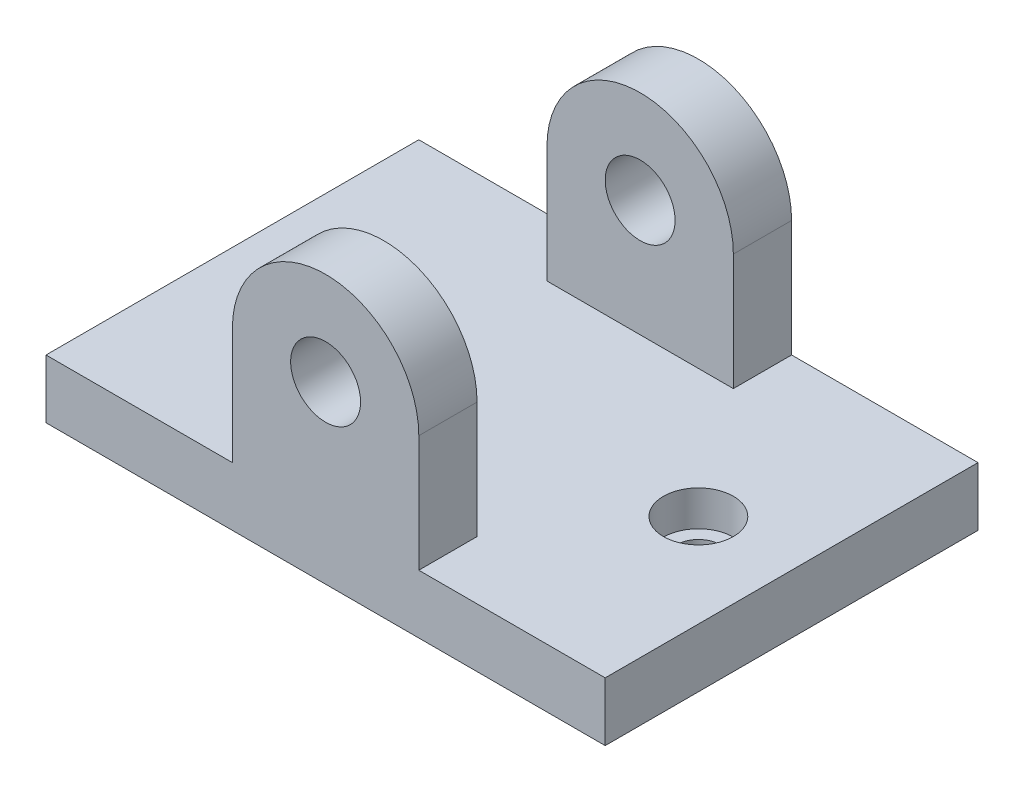
SolidWorks part; units mm, degrees
material "Plain Carbon Steel"
ref_plane "Front Plane" through (0, 0, 0) normal (0, 0, 1) x (1, 0, 0)
ref_plane "Top Plane" through (0, 0, 0) normal (0, 1, 0) x (1, 0, 0)
ref_plane "Right Plane" through (0, 0, 0) normal (1, 0, 0) x (0, 0, -1)
other "Configuration Table"
sketch "Sketch1" plane through (0, 0, 0) normal (0, 1, 0) x (1, 0, 0)
  line L1 (-76.2, 50.8) -> (76.2, 50.8)
  line L2 (-76.2, 50.8) -> (-76.2, -50.8)
  line L3 (-76.2, -50.8) -> (76.2, -50.8)
  line L4 (76.2, 50.8) -> (76.2, -50.8)
  line L5 (-76.2, 50.8) -> (76.2, -50.8) construction
  line L6 (-76.2, -50.8) -> (76.2, 50.8) construction
  point P0 (0, 0)
  dimension "D1" = 101.6
  dimension "D2" = 152.4
extrude "Boss-Extrude1" add sketch "Sketch1" along normal blind 16.002
sketch "Sketch2" plane through (0, 0, 0) normal (0, 1, 0) x (1, 0, 0)
  line L0 (-76.2, 0) -> (76.2, 0) construction
  line L1 (-76.2, 50.8) -> (-76.2, -50.8) construction
  line L2 (76.2, -50.8) -> (76.2, 50.8) construction
  line L3 (-50.8, 50.8) -> (-50.8, -50.8) construction
  line L4 (76.2, 50.8) -> (-76.2, 50.8) construction
  line L5 (-76.2, -50.8) -> (76.2, -50.8) construction
  line L6 (50.8, 50.8) -> (50.8, -50.8) construction
  dimension "D1" = 50.8
  dimension "D2" = 25.4
  dimension "D3" = 25.4
hole_wizard "CBORE for #0 Binding Head Machine Screw1" positions "Sketch3" profile "Sketch4" counterbore size "#0" standard "ANSI Inch" end condition through all
sketch "Sketch3" plane through (0, 16.002, 0) normal (0, 1, 0) x (1, 0, 0)
  line L0 (-76.2, 0) -> (76.2, 0) construction
  line L1 (-50.8, 50.8) -> (-50.8, -50.8) construction
  line L2 (50.8, 50.8) -> (50.8, -50.8) construction
  point P0 (-50.8, 0)
  point P6 (50.8, 0)
sketch "Sketch4" plane through (-50.8, 16.002, 0) normal (1, 0, 0) x (0, 0, 1)
  line L0 (0, 0) -> (0, 16.002)
  line L1 (0, 16.002) -> (5.9563, 16.002)
  line L3 (5.9563, 16.002) -> (5.9563, 9.652)
  line L4 (5.9563, 9.652) -> (9.525, 9.652)
  line L5 (9.525, 9.652) -> (9.525, 0)
  line L7 (9.525, 0) -> (0, 0)
  line L11 (0, -6.35) -> (0, 107.95) construction
  dimension "Thru Hole Dia." = 11.9126
  dimension "Thru Hole Depth" = 16.002
  dimension "C'Bore Dia." = 19.05
  dimension "C'Bore Depth" = 9.652
sketch "Sketch7" plane through (0, 0, 50.8) normal (0, 0, 1) x (1, 0, 0)
  line L0 (-25.4, 16.002) -> (-25.4, 47.752)
  line L1 (-76.2, 16.002) -> (76.2, 16.002) construction
  line L2 (25.4, 47.752) -> (25.4, 16.002)
  line L3 (25.4, 16.002) -> (-25.4, 16.002)
  line L4 (-76.2, 0) -> (76.2, 0) construction
  line L5 (-76.2, 16.002) -> (-76.2, 0) construction
  arc A0 (-25.4, 47.752) -> (25.4, 47.752) centre (0, 47.752) cw
  dimension "D1" = 47.752
  dimension "D2" = 50.8
  dimension "D3" = 50.8
extrude "Boss-Extrude2" add sketch "Sketch7" against normal blind 15.875
mirror "Mirror1" about plane through (0, 0, 0) normal (0, 0, 1) of "Boss-Extrude2"
sketch "Sketch8" plane through (0, 0, 50.8) normal (0, 0, 1) x (1, 0, 0)
  circle A0 centre (0, 47.752) radius 9.525
  dimension "D1" = 19.05
extrude "Cut-Extrude1" cut sketch "Sketch8" against normal through all
